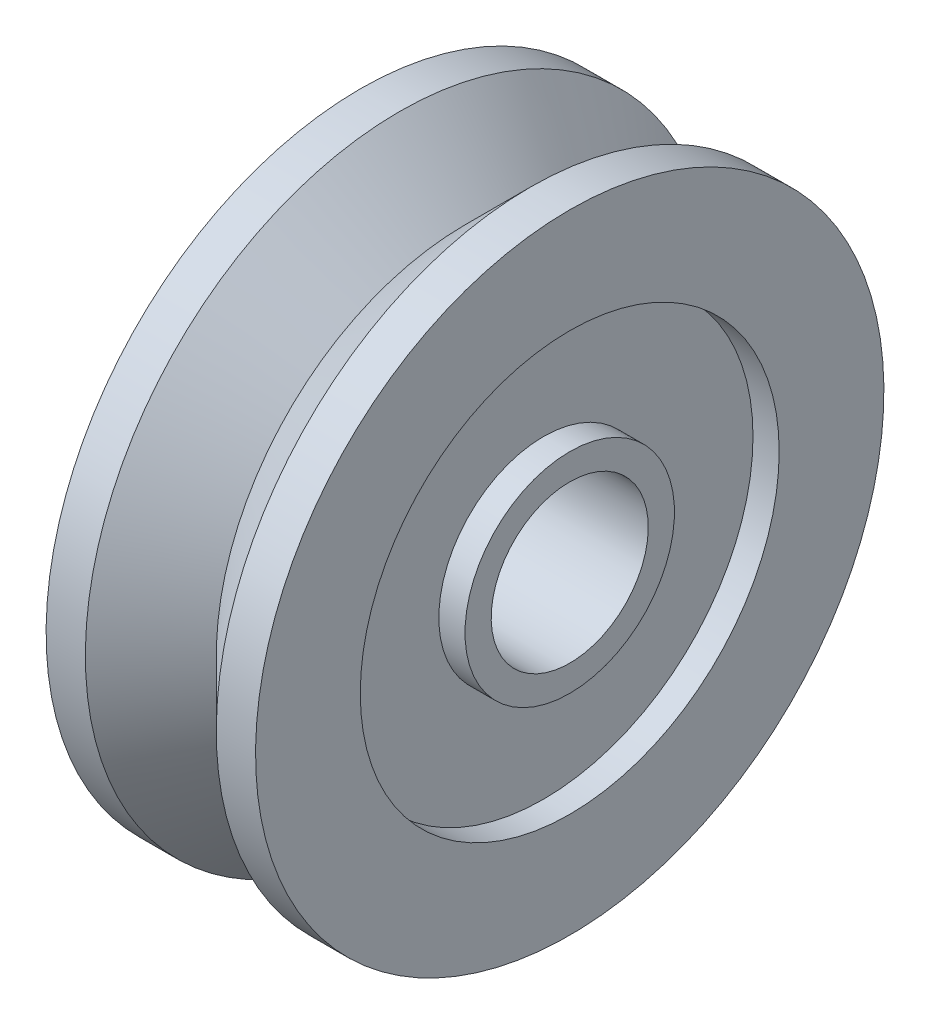
SolidWorks part; units mm, degrees
material "1023 Arkusz stali węglowej (SS)"
ref_plane "Płaszczyzna przednia" through (0, 0, 0) normal (0, 0, 1) x (1, 0, 0)
ref_plane "Płaszczyzna górna" through (0, 0, 0) normal (0, 1, 0) x (1, 0, 0)
ref_plane "Płaszczyzna prawa" through (0, 0, 0) normal (1, 0, 0) x (0, 0, -1)
sketch "Szkic1" plane through (0, 0, 0) normal (0, 0, 1) x (1, 0, 0)
  line L0 (0, 1.5) -> (0, 10.0786) construction
  line L1 (0, 4.75) -> (-1.25, 6)
  line L2 (-1.25, 6) -> (-2, 6)
  line L3 (-2, 6) -> (-2, 4)
  line L4 (-2, 4) -> (-1.5, 4)
  line L5 (-1.5, 4) -> (-1.5, 2)
  line L6 (-1.5, 2) -> (-2, 2)
  line L7 (-2, 2) -> (-2, 1.5)
  line L8 (-2, 1.5) -> (2, 1.5)
  line L9 (0, 0) -> (-2, 0) construction
  line L10 (-2, 0) -> (-2, 1.5) construction
  line L11 (2, 2) -> (2, 1.5)
  line L12 (1.5, 2) -> (2, 2)
  line L13 (1.5, 4) -> (1.5, 2)
  line L14 (2, 4) -> (1.5, 4)
  line L15 (2, 6) -> (2, 4)
  line L16 (1.25, 6) -> (2, 6)
  line L17 (0, 4.75) -> (1.25, 6)
  dimension "D2" = 45
  dimension "D1" = 6
  dimension "D3" = 4
  dimension "D4" = 2
  dimension "D5" = 1.5
  dimension "D6" = 0.5
  dimension "D7" = 0.75
  dimension "D8" = 0.5
revolve "Obrót1" add sketch "Szkic1" angle 360 about L9
